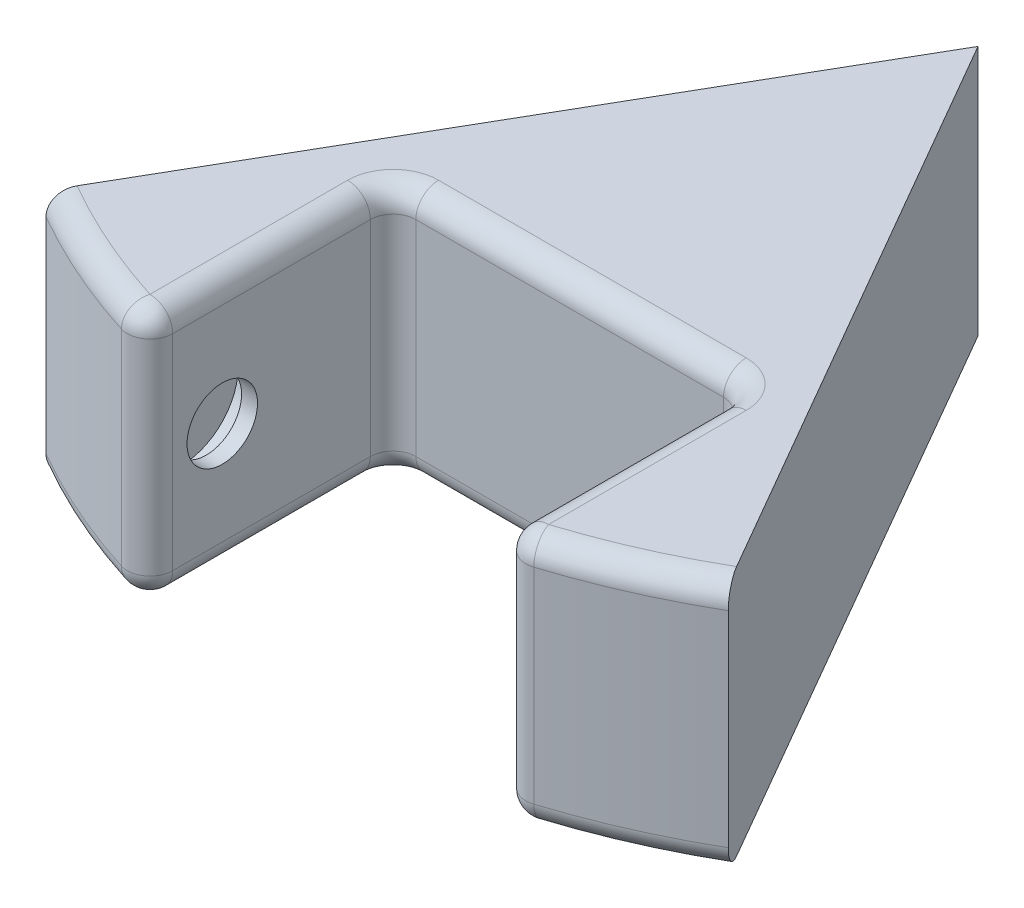
SolidWorks part; units mm, degrees
ref_plane "Front Plane" through (0, 0, 0) normal (0, 0, 1) x (1, 0, 0)
ref_plane "Top Plane" through (0, 0, 0) normal (0, 1, 0) x (1, 0, 0)
ref_plane "Right Plane" through (0, 0, 0) normal (1, 0, 0) x (0, 0, -1)
sketch "Sketch2" plane through (0, 0, 0) normal (0, 1, 0) x (1, 0, 0)
  line L0 (0, 0) -> (0, -76.2) construction
  line L1 (-38.1, -65.9911) -> (0, 0)
  line L2 (0, 0) -> (0, -76.2)
  arc A0 (0, -76.2) -> (-38.1, -65.9911) centre (0, 0) cw
  dimension "D1" = 76.2
extrude "Boss-Extrude1" add sketch "Sketch2" along normal blind 28
sketch "Sketch3" plane through (0, 0, 0) normal (0, 1, 0) x (1, 0, 0)
  line L0 (-38.1, -65.9911) -> (0, -76.2) construction
  line L7 (0, 0) -> (-19.05, -71.0956) construction
  line L8 (-19.05, -71.0956) -> (-19.722, -73.6035) construction
  line L10 (-19.722, -73.6035) -> (19.722, -73.6035) construction
  line L11 (19.722, -73.6035) -> (53.8815, -53.8815) construction
  line L12 (53.8815, -53.8815) -> (73.6035, -19.722) construction
  line L13 (73.6035, -19.722) -> (73.6035, 19.722) construction
  line L14 (73.6035, 19.722) -> (53.8815, 53.8815) construction
  line L15 (53.8815, 53.8815) -> (19.722, 73.6035) construction
  line L16 (19.722, 73.6035) -> (-19.722, 73.6035) construction
  line L17 (-19.722, 73.6035) -> (-53.8815, 53.8815) construction
  line L18 (-53.8815, 53.8815) -> (-73.6035, 19.722) construction
  line L19 (-73.6035, 19.722) -> (-73.6035, -19.722) construction
  line L20 (-73.6035, -19.722) -> (-53.8815, -53.8815) construction
  line L21 (-53.8815, -53.8815) -> (-19.722, -73.6035) construction
  circle A0 centre (0, 0) radius 76.2 construction
  circle A1 centre (0, 0) radius 76.2 construction
sketch "Sketch4" plane through (0, 28, 0) normal (0, 1, 0) x (1, 0, 0)
  line L2 (-19.722, -73.6035) -> (-19.722, -45.6036)
  line L3 (-19.722, -45.6036) -> (19.722, -45.6036)
  line L4 (19.722, -73.6035) -> (19.722, -45.6036)
  line L7 (-19.722, -73.6035) -> (-19.722, -89.0834)
  line L8 (-19.722, -89.0834) -> (19.722, -89.0834)
  line L9 (19.722, -73.6035) -> (19.722, -89.0834)
  dimension "D1" = 28
  dimension "D2" = 39.444
extrude "Cut-Extrude1" cut sketch "Sketch4" against normal through all both and the other way through all
sketch "Sketch5" plane through (-19.722, 0, 0) normal (1, 0, 0) x (0, 0, -1)
  line L0 (-73.6035, 28) -> (-45.6036, 0) construction
  line L1 (-45.6036, 28) -> (-73.6035, 0) construction
  line L3 (-59.6036, 14) -> (-64.6836, 14) construction
  circle A2 centre (-64.6836, 14) radius 6.35
  dimension "D2" = 12.7
  dimension "D1" = 5.08
extrude "Cut-Extrude2" cut sketch "Sketch5" against normal blind 4.572
sketch "Sketch6" plane through (-24.294, 0, 0) normal (1, 0, 0) x (0, 0, -1)
  line L0 (-68.3666, 14) -> (-68.4936, 14) construction
  line L1 (-71.0336, 14) -> (-70.7796, 14) construction
  line L2 (-64.6836, 17.81) -> (-64.6836, 20.096) construction
  line L3 (-64.6836, 14) -> (-45.6036, 14) construction
  line L4 (-45.6036, 0) -> (-45.6036, 28) construction
  line L5 (-64.6836, 14) -> (-61.7723, 18.0071) construction
  circle A0 centre (-64.6836, 14) radius 3.683
  circle A1 centre (-64.6836, 14) radius 3.81
  circle A2 centre (-64.6836, 14) radius 6.35 construction
  circle A3 centre (-64.6836, 14) radius 6.35 construction
  circle A4 centre (-64.6836, 14) radius 6.096
  circle A5 centre (-64.6836, 18.953) radius 1.143
  circle A6 centre (-61.7723, 18.0071) radius 1.143
  circle A7 centre (-59.973, 15.5306) radius 1.143
  circle A8 centre (-59.973, 12.4694) radius 1.143
  circle A9 centre (-61.7723, 9.9929) radius 1.143
  circle A10 centre (-64.6836, 9.047) radius 1.143
  circle A11 centre (-67.5949, 9.9929) radius 1.143
  circle A12 centre (-69.3941, 12.4694) radius 1.143
  circle A13 centre (-69.3941, 15.5306) radius 1.143
  circle A14 centre (-67.5949, 18.0071) radius 1.143
  point P38 (-64.6836, 14)
  dimension "D1" = 7.366
  dimension "D4" = 2.286
  dimension "D5" = 10
  dimension "D6" = 2.286
  dimension "D7" = 2.286
  dimension "D2" = 0.127
  dimension "D3" = 0.254
  dimension "D8" = 19.08
  dimension "D9" = 4.953
sketch "Sketch7" plane through (0, 0, 45.6036) normal (0, 0, 1) x (1, 0, 0)
  line L0 (-24.294, 14) -> (-21.5, 14) construction
  line L1 (-21.5, 14) -> (-19.722, 14) construction
  line L2 (-19.722, 0) -> (-19.722, 28) construction
  line L3 (-24.294, 14) -> (0, 14) construction
  line L4 (0, 28) -> (0, 0) construction
  dimension "D1" = 2.794
  dimension "D2" = 1.778
sketch "Sketch8" plane through (-19.722, 0, 0) normal (1, 0, 0) x (0, 0, -1)
  circle A0 centre (-64.6836, 14) radius 6.35
  circle A1 centre (-64.6836, 14) radius 3.937
  dimension "D1" = 7.874
extrude "Boss-Extrude4" add sketch "Sketch8" against normal blind 1.778
mirror "Mirror1" about plane through (0, 28, 0) normal (-1, 0, 0) of "Boss-Extrude1", "Boss-Extrude4", "Cut-Extrude2", "Cut-Extrude1"
fillet "Fillet1" radius 2.54 14 edges at (-19.722, 14, 73.6035) (19.722, 14, 73.6035) (19.722, 0, 59.6036) (-19.722, 0, 59.6036) (-19.722, 28, 59.6036) (19.722, 28, 59.6036) (-19.722, 14, 45.6036) (19.722, 14, 45.6036) (0, 0, 45.6036) (0, 28, 45.6036) (-29.1605, 0, 70.3996) (-29.1605, 28, 70.3996) (29.1605, 0, 70.3996) (29.1605, 28, 70.3996)
sketch "Sketch10" plane through (0, 0, 0) normal (1, 0, 0) x (0, 0, -1)
  line L1 (0, 0) -> (-72.6366, 0)
  line L2 (0, 0) -> (0, 28)
  line L3 (0, 28) -> (-72.6366, 28)
  line L4 (-72.6366, 0) -> (-72.6366, 28)
  line L5 (0, 0) -> (-72.6366, 28) construction
  line L6 (0, 28) -> (-72.6366, 0) construction
  point P4 (-36.3183, 14)
